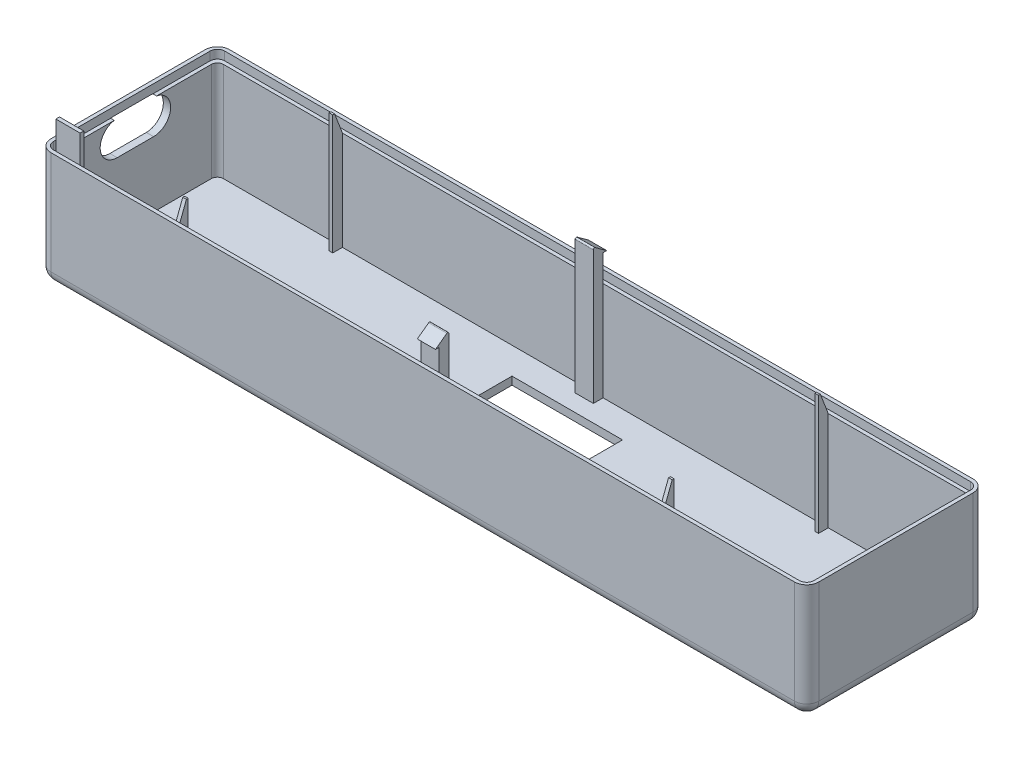
SolidWorks part; units mm, degrees
ref_plane "Front Plane" through (0, 0, 0) normal (0, 0, 1) x (1, 0, 0)
ref_plane "Top Plane" through (0, 0, 0) normal (0, 1, 0) x (1, 0, 0)
ref_plane "Right Plane" through (0, 0, 0) normal (1, 0, 0) x (0, 0, -1)
sketch "Sketch1" plane through (0, 0, 0) normal (0, 1, 0) x (1, 0, 0)
  line L1 (-80.2894, -18.669) -> (80.2894, -18.669)
  line L2 (-80.2894, -18.669) -> (-80.2894, 18.669)
  line L3 (-80.2894, 18.669) -> (80.2894, 18.669)
  line L4 (80.2894, -18.669) -> (80.2894, 18.669)
  line L5 (-80.2894, -18.669) -> (80.2894, 18.669) construction
  line L6 (-80.2894, 18.669) -> (80.2894, -18.669) construction
  point P0 (0, 0)
  dimension "D1" = 160.5788
  dimension "D2" = 37.338
extrude "Boss-Extrude1" add sketch "Sketch1" along normal blind 24.13
sketch "Sketch2" plane through (0, 24.13, 0) normal (0, 1, 0) x (1, 0, 0)
  line L0 (-80.2894, 18.669) -> (-80.2894, -18.669) construction
  line L1 (-78.7654, 17.145) -> (78.7654, 17.145)
  line L2 (-78.7654, 17.145) -> (-78.7654, -17.145)
  line L3 (-78.7654, -17.145) -> (78.7654, -17.145)
  line L4 (78.7654, 17.145) -> (78.7654, -17.145)
  line L5 (-78.7654, 17.145) -> (78.7654, -17.145) construction
  line L6 (-78.7654, -17.145) -> (78.7654, 17.145) construction
  line L7 (-80.2894, -18.669) -> (80.2894, -18.669) construction
  point P0 (0, 0)
  dimension "D1" = 1.524
  dimension "D2" = 1.524
extrude "Cut-Extrude3" cut sketch "Sketch2" against normal offset from surface (22.479 mm away) 1.651 up to face at (0, 0, 0)
fillet "Fillet1" radius 2.54 8 edges at (80.2894, 0, 0) (80.2894, 12.065, -18.669) (0, 0, -18.669) (0, 0, 18.669) (-80.2894, 0, 0) (-80.2894, 12.065, -18.669) (-80.2894, 12.065, 18.669) (80.2894, 12.065, 18.669)
fillet "Fillet2" radius 1.27 4 edges at (78.7654, 12.8905, -17.145) (78.7654, 12.8905, 17.145) (-78.7654, 12.8905, -17.145) (-78.7654, 12.8905, 17.145)
sketch "Sketch3" plane through (-80.2894, 0, 0) normal (-1, 0, 0) x (0, 0, 1)
  line L0 (3.81, 18.8493) -> (-3.81, 18.8493) construction
  line L1 (3.81, 15.2933) -> (-3.81, 15.2933)
  line L2 (3.81, 22.4053) -> (-3.81, 22.4053)
  line L3 (-16.129, 24.13) -> (16.129, 24.13) construction
  line L4 (0, 24.13) -> (0, -3.1618) construction
  arc A0 (3.81, 15.2933) -> (3.81, 22.4053) centre (3.81, 18.8493) ccw
  arc A1 (-3.81, 22.4053) -> (-3.81, 15.2933) centre (-3.81, 18.8493) ccw
  point P2 (0, 18.8493)
  dimension "D1" = 3.556
  dimension "D2" = 7.62
  dimension "D3" = 1.7247
extrude "Cut-Extrude4" cut sketch "Sketch3" against normal up to next
sketch "Sketch4" plane through (0, 24.13, 0) normal (0, 1, 0) x (1, 0, 0)
  line L0 (-80.2894, 16.129) -> (-80.2894, -16.129) construction
  line L1 (-79.5274, -17.907) -> (79.5274, -17.907)
  line L2 (-79.5274, -17.907) -> (-79.5274, 17.907)
  line L3 (-79.5274, 17.907) -> (79.5274, 17.907)
  line L4 (79.5274, -17.907) -> (79.5274, 17.907)
  line L5 (77.7494, 18.669) -> (-77.7494, 18.669) construction
  line L6 (80.2894, -16.129) -> (80.2894, 16.129) construction
  line L7 (-77.7494, -18.669) -> (77.7494, -18.669) construction
  dimension "D1" = 0.762
  dimension "D2" = 0.762
  dimension "D3" = 0.762
  dimension "D4" = 0.762
extrude "Cut-Extrude5" cut sketch "Sketch4" against normal blind 1.778
fillet "Fillet3" radius 1.524 4 edges at (79.5274, 23.241, -17.907) (-79.5274, 23.241, -17.907) (-79.5274, 23.241, 17.907) (79.5274, 23.241, 17.907)
sketch "Sketch5" plane through (0, 22.352, 0) normal (0, 1, 0) x (1, 0, 0)
  line L0 (-78.0034, -17.907) -> (78.0034, -17.907) construction
  line L1 (-72.4154, -17.907) -> (-77.4954, -17.907)
  line L2 (-72.4154, -17.907) -> (-72.4154, -17.145)
  line L3 (-72.4154, -17.145) -> (-77.4954, -17.145)
  line L4 (-77.4954, -17.907) -> (-77.4954, -17.145)
  line L5 (-77.4954, -17.145) -> (77.4954, -17.145) construction
  dimension "D1" = 5.08
extrude "Boss-Extrude2" add sketch "Sketch5" along normal blind 7.62
sketch "Sketch6" plane through (0, 1.651, 0) normal (0, 1, 0) x (1, 0, 0)
  line L0 (77.4954, 17.145) -> (-77.4954, 17.145) construction
  line L1 (-53.3654, 17.145) -> (-52.6034, 17.145)
  line L2 (-53.3654, 17.145) -> (-53.3654, 15.113)
  line L3 (-53.3654, 15.113) -> (-52.6034, 15.113)
  line L4 (-52.6034, 17.145) -> (-52.6034, 15.113)
  line L5 (-78.7654, 15.875) -> (-78.7654, -15.875) construction
  dimension "D1" = 0.762
  dimension "D2" = 2.032
  dimension "D3" = 25.4
extrude "Boss-Extrude3" add sketch "Sketch6" along normal offset from surface (25.019 mm away) 2.54 up to face at (-14.9911, 24.13, 3.5814) offset beyond the face yes
pattern_linear "LPattern1" count 2 spacing 101.6 along (1, 0, 0) count 2 spacing 32.258 along (0, 0, 1) of "Boss-Extrude3"
sketch "Sketch7" plane through (48.9966, 0, 0) normal (1, 0, 0) x (0, 0, -1)
  line L0 (17.145, 22.352) -> (15.494, 26.67)
  line L1 (17.145, 26.67) -> (15.113, 26.67) construction
  line L2 (15.494, 26.67) -> (17.145, 26.67)
  line L3 (17.145, 26.67) -> (17.145, 22.352)
  dimension "D1" = 0.381
extrude "Cut-Extrude6" cut sketch "Sketch7" against normal up to surface (102.362 mm away) up to face at (-53.3654, 15.7988, -16.3322)
mirror "Mirror1" about plane through (0, 0, 0) normal (0, 0, 1) of "Cut-Extrude6"
sketch "Sketch8" plane through (0, 1.651, 0) normal (0, 1, 0) x (1, 0, 0)
  line L0 (0, 0) -> (0, 21.7842) construction
  line L1 (1.905, -17.145) -> (-1.905, -17.145)
  line L2 (1.905, -17.145) -> (1.905, -15.113)
  line L3 (1.905, -15.113) -> (-1.905, -15.113)
  line L4 (-1.905, -17.145) -> (-1.905, -15.113)
  line L5 (1.905, 15.113) -> (-1.905, 15.113)
  line L6 (1.905, 15.113) -> (1.905, 17.145)
  line L7 (1.905, 17.145) -> (-1.905, 17.145)
  line L8 (-1.905, 15.113) -> (-1.905, 17.145)
  line L9 (-52.6034, -17.145) -> (48.2346, -17.145) construction
  line L10 (48.2346, 17.145) -> (-52.6034, 17.145) construction
  dimension "D1" = 3.81
  dimension "D2" = 2.032
extrude "Boss-Extrude4" add sketch "Sketch8" along normal offset from surface (26.289 mm away) 3.81 up to face at (-14.9911, 24.13, 3.5814) offset beyond the face yes
sketch "Sketch9" plane through (1.905, 0, 0) normal (1, 0, 0) x (0, 0, -1)
  line L0 (-15.113, 27.94) -> (-17.907, 27.94)
  line L1 (-17.907, 27.94) -> (-15.113, 29.972)
  line L2 (-15.113, 29.972) -> (-15.113, 27.94)
  line L3 (-17.145, 27.94) -> (-17.145, 22.352) construction
  dimension "D1" = 0.762
  dimension "D2" = 2.032
extrude "Boss-Extrude9" add sketch "Sketch9" against normal blind 3.81
fillet "Fillet4" radius 0.254 1 edges at (0, 29.972, 15.113)
mirror "Mirror2" about plane through (0, 0, 0) normal (0, 0, 1) of "Fillet4", "Boss-Extrude9"
sketch "Sketch10" plane through (0, 0, 0) normal (0, -1, 0) x (1, 0, 0)
  line L0 (-13.589, 0) -> (13.589, 0) construction
  line L1 (0, 0) -> (0, -42.7568) construction
  line L2 (11.557, 11.557) -> (-11.557, 11.557)
  line L3 (11.557, 11.557) -> (11.557, -11.557)
  line L4 (11.557, -11.557) -> (-11.557, -11.557)
  line L5 (-11.557, 11.557) -> (-11.557, -11.557)
  line L6 (11.557, 11.557) -> (-11.557, -11.557) construction
  line L7 (11.557, -11.557) -> (-11.557, 11.557) construction
  circle A1 centre (-13.589, 0) radius 0.889
  circle A2 centre (13.589, 0) radius 0.889
  point P0 (0, 0)
  dimension "D1" = 23.114
  dimension "D4" = 1.778
  dimension "D2" = 27.178
  dimension "D5" = 23.114
extrude "Cut-Extrude7" cut sketch "Sketch10" against normal through all
